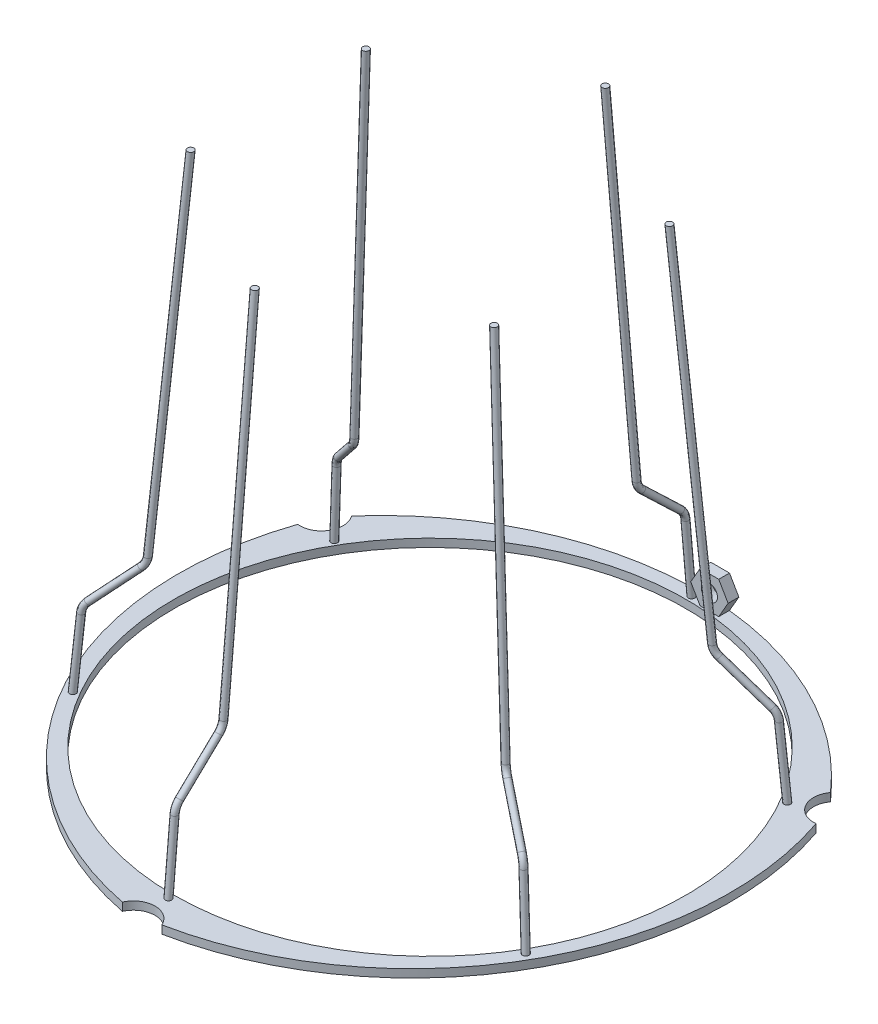
SolidWorks part; units mm, degrees
material "AISI 304"
ref_plane "Спереди" through (0, 0, 0) normal (0, 0, 1) x (1, 0, 0)
ref_plane "Сверху" through (0, 0, 0) normal (0, 1, 0) x (1, 0, 0)
ref_plane "Справа" through (0, 0, 0) normal (1, 0, 0) x (0, 0, -1)
ref_axis "Ось1" through (0, 50, 0) along (0, -1, 0)
sketch "Эскиз1" plane through (0, 0, 0) normal (0, 1, 0) x (1, 0, 0)
  line L0 (0, 47.5) -> (0, 50) construction
  line L1 (41.1362, 23.75) -> (43.3013, 25) construction
  line L2 (41.1362, -23.75) -> (43.3013, -25) construction
  line L3 (0, -47.5) -> (0, -50) construction
  line L4 (-41.1362, -23.75) -> (-43.3013, -25) construction
  line L5 (-41.1362, 23.75) -> (-43.3013, 25) construction
  line L6 (-41.1362, 23.75) -> (-46.7654, 27) construction
  line L7 (41.1362, 23.75) -> (46.7654, 27) construction
  line L8 (0, -47.5) -> (0, -54) construction
  circle A0 centre (0, 0) radius 47.5
  arc A1 (-46.7654, 27) -> (46.7654, 27) centre (0, -9.0435) cw
  arc A2 (46.7654, 27) -> (0, -54) centre (-7.8319, 4.5217) cw
  arc A3 (0, -54) -> (-46.7654, 27) centre (7.8319, 4.5217) cw
  circle A5 centre (-47.6314, 27.5) radius 4
  circle A6 centre (47.6314, 27.5) radius 4
  circle A7 centre (0, -55) radius 4
  point P22 (0, 48.75)
  dimension "D1" = 95
  dimension "D7" = 3.5
  dimension "D8" = 8
  dimension "D2" = 2.5
  dimension "D4" = 6.5
  dimension "D3" = 6
  dimension "D5" = 3
  dimension "D6" = 3
  dimension "D9" = 3
sketch "Эскиз2" plane through (0, 0, 0) normal (0, 1, 0) x (1, 0, 0)
  arc A0 (46.7654, 27) -> (-46.7654, 27) centre (0, -9.0435) ccw construction
  circle A1 centre (0, 0) radius 47.5
  circle A2 centre (0, 0) radius 47.5
  circle A3 centre (47.6314, 27.5) radius 4
  arc A4 (44.4076, 29.8679) -> (48.0702, 23.5241) centre (47.6314, 27.5) ccw
  circle A5 centre (-47.6314, 27.5) radius 4
  arc A6 (-48.0702, 23.5241) -> (-44.4076, 29.8679) centre (-47.6314, 27.5) ccw
  circle A7 centre (0, -55) radius 4
  arc A8 (3.6626, -53.3921) -> (-3.6626, -53.3921) centre (0, -55) ccw
  arc A9 (0, -54) -> (46.7654, 27) centre (-7.8319, 4.5217) ccw construction
  arc A10 (-46.7654, 27) -> (0, -54) centre (7.8319, 4.5217) ccw construction
  arc A11 (44.4076, 29.8679) -> (-44.4076, 29.8679) centre (0, -9.0435) ccw
  arc A12 (3.6626, -53.3921) -> (48.0702, 23.5241) centre (-7.8319, 4.5217) ccw
  arc A13 (-48.0702, 23.5241) -> (-3.6626, -53.3921) centre (7.8319, 4.5217) ccw
  dimension "D1" = 0
  dimension "D2" = 0
  dimension "D3" = 0
  dimension "D4" = 0
extrude "Бобышка-Вытянуть1" add sketch "Эскиз2" along normal blind 1.5
sketch "Эскиз3" plane through (0, 0, 0) normal (1, 0, 0) x (0, 0, -1)
  line L0 (-48.5, 1.5) -> (-47.3626, 14.5)
  line L1 (-46.4462, 16.4079) -> (-39.2149, 23.3151)
  line L2 (-38.2985, 25.223) -> (-32.5, 91.5)
  line L3 (-48.5, 1.5) -> (0, 1.5) construction
  line L4 (23.5241, 1.5) -> (-53.3921, 1.5) construction
  line L5 (0, 0) -> (0, 38.3248) construction
  arc A0 (-39.2149, 23.3151) -> (-38.2985, 25.223) centre (-41.2871, 25.4844) ccw
  arc A1 (-47.3626, 14.5) -> (-46.4462, 16.4079) centre (-44.3741, 14.2385) cw
  point P16 (-47.5, 1.5)
  dimension "D1" = 3
  dimension "D2" = 1
  dimension "D3" = 85
  dimension "D4" = 13
  dimension "D5" = 10
  dimension "D6" = 90
  dimension "D7" = 65
  dimension "D8" = 76.597
sketch "Эскиз4" plane through (0, 1.5, 0) normal (0, 1, 0) x (1, 0, 0)
  circle A0 centre (0, -48.5) radius 0.6
  dimension "D1" = 1.2
sweep "По траектории1" add profiles "Эскиз4" path "Эскиз3"
pattern_circular "Круговой массив1" count 6 over 360 about axis through (0, 50, 0) along (0, -1, 0) of bodies 104
ref_plane "Плоскость1" through (0, 0, -48.75) normal (0, 0, 1) x (1, 0, 0)
sketch "Эскиз5" plane through (0, 0, -48.75) normal (0, 0, 1) x (1, 0, 0)
  line L0 (-3.6626, 1.5) -> (-51.2116, 1.5) construction
  line L1 (5.7962, 1.5) -> (7.5282, 4.5)
  line L2 (7.5282, 4.5) -> (5.7962, 7.5)
  line L3 (5.7962, 7.5) -> (2.3321, 7.5)
  line L4 (2.3321, 7.5) -> (0.6, 4.5)
  line L5 (0.6, 4.5) -> (2.3321, 1.5)
  line L6 (2.3321, 1.5) -> (5.7962, 1.5)
  line L8 (0.6, 1.5) -> (0.6, 14.5) construction
  circle A0 centre (4.0641, 4.5) radius 3 construction
  circle A1 centre (4.0641, 4.5) radius 1.5
  point P9 (-0.3773, 10.9621)
  point P10 (0, 0)
  point P13 (0, 0)
  point P14 (1.1783, 4.5)
  point P15 (0, 0)
  point P16 (0, 0)
  point P17 (0, 0)
  dimension "D2" = 3
  dimension "D1" = 6
extrude "Бобышка-Вытянуть2" add sketch "Эскиз5" along normal mid plane 2 separate body
cosmetic thread "Условное изображение резьбы1" parameters "D2"=4
sketch "Эскиз6" plane through (0, 91.5, 0) normal (0, 1, 0) x (1, 0, 0)
  line L0 (-0.6, -32.5) -> (0.6, -32.5) construction
  circle A0 centre (0, -32.5) radius 0.6 construction
  point P4 (0.6, -32.5)
  point P6 (-0.5994, -32.5262)
  point P7 (0, 0)
ref_plane "Плоскость2" through (0, 3.5168, 40.1975) normal (0, -0.0872, -0.9962) x (-1, 0, 0)
